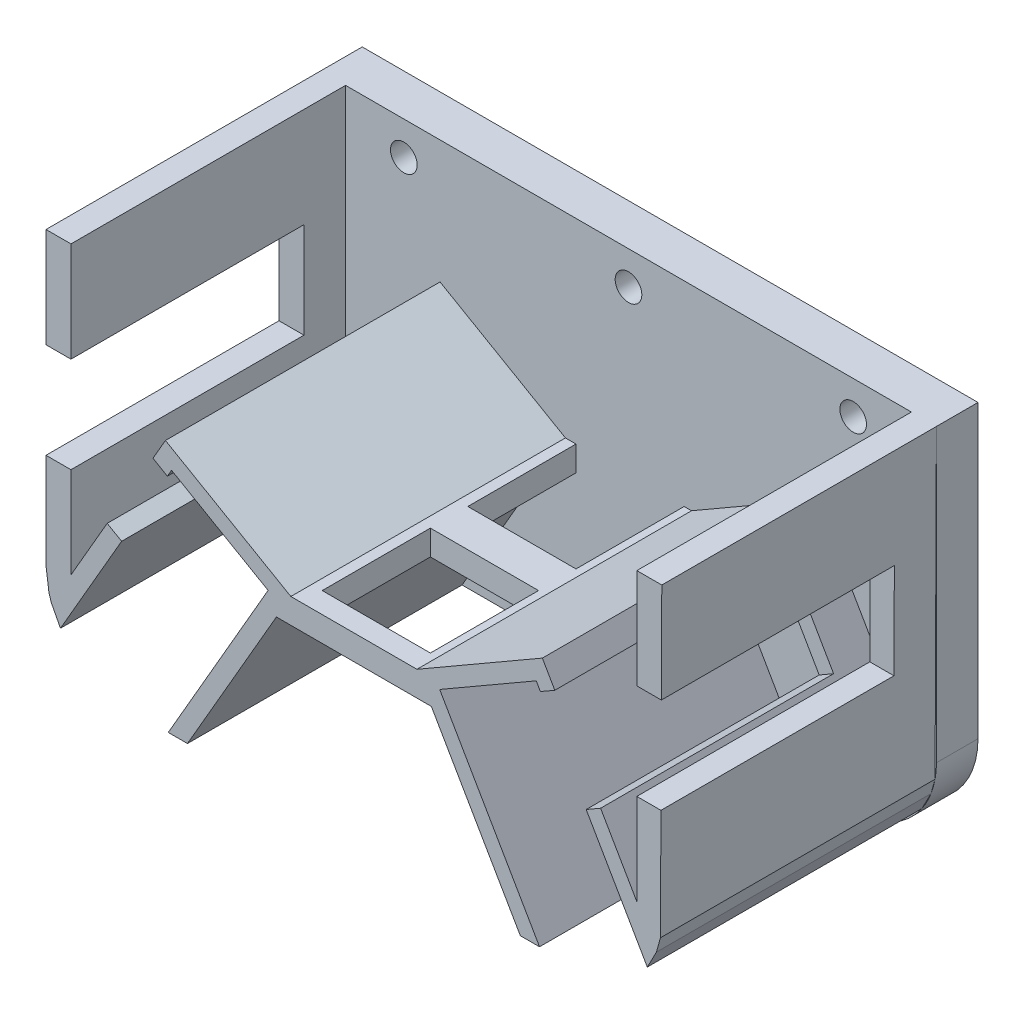
SolidWorks part; units mm, degrees
ref_plane "前视基准面" through (0, 0, 0) normal (0, 0, 1) x (1, 0, 0)
ref_plane "上视基准面" through (0, 0, 0) normal (0, 1, 0) x (1, 0, 0)
ref_plane "右视基准面" through (0, 0, 0) normal (1, 0, 0) x (0, 0, -1)
other "Configuration Table"
sketch "草图1" plane through (0, 0, 0) normal (0, 0, 1) x (1, 0, 0)
  line L0 (-37, -22.5) -> (37, -22.5)
  line L1 (-37, 22.5) -> (37, 22.5)
  line L2 (-37, 22.5) -> (-37, -22.5)
  line L4 (37, 22.5) -> (37, -22.5)
  line L5 (0, -22.5) -> (0, 22.5) construction
  line L6 (-37, 0) -> (37, 0) construction
  point P0 (0, 0)
  point P8 (37, -22.5)
  dimension "D1" = 74
  dimension "D2" = 45
extrude "凸台-拉伸1" add sketch "草图1" along normal blind 5
fillet "圆角1" radius 10 1 edges at (-37, -22.5, 2.5)
fillet "圆角2" radius 10 1 edges at (37, -22.5, 2.5)
sketch "草图4" plane through (0, 0, 5) normal (0, 0, 1) x (1, 0, 0)
  line L0 (-35.2618, -18.1341) -> (-21.9141, 4.9846)
  line L1 (-21.9141, 4.9846) -> (-10.3094, -1.7154)
  line L2 (-10.3094, -1.7154) -> (-22.3094, -22.5)
  line L4 (0, 0) -> (0, 22.5) construction
  line L6 (-20, -22.5) -> (-7.5774, -0.9833)
  line L7 (-27, -22.5) -> (27, -22.5) construction
  line L8 (-7.5774, -0.9833) -> (-22.6462, 7.7167)
  line L9 (-22.6462, 7.7167) -> (-36.3563, -16.0299)
  line L11 (-22.3094, -22.5) -> (-20, -22.5)
  line L20 (-36.3563, -16.0299) -> (-35.2618, -18.1341)
  line L21 (36.3563, -16.0299) -> (35.2618, -18.1341)
  line L22 (22.3094, -22.5) -> (20, -22.5)
  line L23 (22.6462, 7.7167) -> (36.3563, -16.0299)
  line L24 (7.5774, -0.9833) -> (22.6462, 7.7167)
  line L25 (20, -22.5) -> (7.5774, -0.9833)
  line L26 (10.3094, -1.7154) -> (22.3094, -22.5)
  line L27 (21.9141, 4.9846) -> (10.3094, -1.7154)
  line L28 (35.2618, -18.1341) -> (21.9141, 4.9846)
  arc A1 (-37, -12.5) -> (-27, -22.5) centre (-27, -12.5) ccw construction
  point P2 (-36.3563, -16.0299)
  point P23 (36.3563, -16.0299)
  dimension "D1" = 13.4
  dimension "D2" = 24
  dimension "D3" = 2
  dimension "D4" = 2
  dimension "D5" = 2
  dimension "D6" = 60
  dimension "D7" = 20
extrude "凸台-拉伸3" add sketch "草图4" along normal blind 33
sketch "草图5" plane through (0, 0, 5) normal (0, 0, 1) x (1, 0, 0)
  line L0 (-7.5774, -0.9833) -> (7.5774, -0.9833)
  line L1 (7.5774, -0.9833) -> (9.3094, -3.9833)
  line L2 (7.5774, -0.9833) -> (20, -22.5) construction
  line L3 (9.3094, -3.9833) -> (-9.3094, -3.9833)
  line L4 (-20, -22.5) -> (-7.5774, -0.9833) construction
  line L5 (-9.3094, -3.9833) -> (-7.5774, -0.9833)
  dimension "D1" = 3
extrude "凸台-拉伸4" add sketch "草图5" along normal blind 33
sketch "草图6" plane through (0, -3.9833, 0) normal (0, -1, 0) x (1, 0, 0)
  line L0 (-20, 5) -> (20, 5) construction
  line L1 (-6.3094, 35.5) -> (6.6906, 35.5)
  line L2 (-6.3094, 35.5) -> (-6.3094, 22.5)
  line L3 (-6.3094, 22.5) -> (6.6906, 22.5)
  line L4 (6.6906, 35.5) -> (6.6906, 22.5)
  line L5 (-6.3094, 18) -> (6.6906, 18)
  line L6 (-6.3094, 18) -> (-6.3094, 5)
  line L7 (-6.3094, 5) -> (6.6906, 5)
  line L8 (6.6906, 18) -> (6.6906, 5)
  line L9 (-9.3094, 38) -> (-9.3094, 5) construction
  line L10 (-9.3094, 38) -> (9.3094, 38) construction
  dimension "D1" = 13
  dimension "D2" = 3
  dimension "D3" = 13
  dimension "D4" = 13
  dimension "D5" = 2.5
  dimension "D6" = 13
extrude "切除-拉伸1" cut sketch "草图6" against normal through all
sketch "草图8" plane through (0, 0, 38) normal (0, 0, 1) x (1, 0, 0)
  line L0 (-29.6462, -4.4077) -> (-24.1462, 5.1186)
  line L1 (-22.6462, 7.7167) -> (-36.3563, -16.0299) construction
  line L2 (-24.1462, 5.1186) -> (-22.4141, 4.1186)
  line L3 (-35.2618, -18.1341) -> (-21.9141, 4.9846) construction
  line L4 (-22.4141, 4.1186) -> (-27.9141, -5.4077)
  line L5 (-27.9141, -5.4077) -> (-29.6462, -4.4077)
  line L6 (0, 0) -> (0, 25.4331) construction
  line L7 (-7.5774, -0.9833) -> (-22.6462, 7.7167) construction
  line L8 (27.9141, -5.4077) -> (29.6462, -4.4077)
  line L9 (22.4141, 4.1186) -> (27.9141, -5.4077)
  line L10 (24.1462, 5.1186) -> (22.4141, 4.1186)
  line L11 (29.6462, -4.4077) -> (24.1462, 5.1186)
  dimension "D1" = 3
  dimension "D2" = 11
extrude "切除-拉伸3" cut sketch "草图8" against normal blind 28
sketch "草图9" plane through (0, 0, 5) normal (0, 0, 1) x (1, 0, 0)
  line L2 (37, 22.5) -> (-37, 22.5) construction
  line L3 (-34, 22.5) -> (-37, 22.5)
  line L7 (0, 0) -> (0, 41.014) construction
  line L8 (36.3563, -16.0299) -> (34, -11.9487)
  line L9 (36.8378, -14.2941) -> (36.3563, -16.0299)
  line L10 (37, 22.5) -> (36.8378, -14.2941)
  line L11 (34, 22.5) -> (37, 22.5)
  line L12 (34, -11.9487) -> (34, 22.5)
  line L13 (-37, 22.5) -> (-37, -12.5)
  line L14 (-37, -12.5) -> (-36.6387, -15.1638)
  line L15 (-36.6387, -15.1638) -> (-36.3563, -16.0299)
  line L16 (-34, 22.5) -> (-34, -11.9487)
  line L17 (-22.6462, 7.7167) -> (-36.3563, -16.0299) construction
  line L18 (-34, -11.9487) -> (-36.3563, -16.0299)
  arc A1 (-37, -12.5) -> (-36.3563, -16.0299) centre (-27, -12.5) ccw construction
  dimension "D1" = 3
extrude "凸台-拉伸5" add sketch "草图9" along normal blind 33
sketch "草图10" plane through (0, 0, 38) normal (0, 0, 1) x (1, 0, 0)
  line L0 (-37, 22.5) -> (-37, -12.5) construction
  line L1 (-37, 10.5) -> (-34, 10.5)
  line L2 (-37, 10.5) -> (-37, -1)
  line L3 (-37, -1) -> (-34, -1)
  line L4 (-34, 10.5) -> (-34, -1)
  line L5 (-34, -11.9487) -> (-34, 22.5) construction
  line L6 (-34, 22.5) -> (-37, 22.5) construction
  line L7 (0, 0) -> (0, 29.9906) construction
  line L8 (34, 10.5) -> (34, -1)
  line L9 (37, -1) -> (34, -1)
  line L10 (37, 10.5) -> (37, -1)
  line L11 (37, 10.5) -> (34, 10.5)
  dimension "D1" = 12
  dimension "D2" = 11.5
extrude "切除-拉伸4" cut sketch "草图10" against normal blind 28
sketch "草图11" plane through (0, 0, 5) normal (0, 0, 1) x (1, 0, 0)
  line L0 (34, 22.5) -> (-34, 22.5) construction
  line L1 (-37, 22.5) -> (-37, 10.5) construction
  circle A0 centre (-27, 18.5) radius 1.6
  circle A1 centre (0, 18.5) radius 1.6
  circle A2 centre (27, 18.5) radius 1.6
  dimension "D2" = 3.2
  dimension "D3" = 10
  dimension "D4" = 3.2
  dimension "D5" = 3.2
  dimension "D9" = 4
  dimension "D1" = 4
  dimension "D6" = 27
  dimension "D7" = 4
  dimension "D8" = 27
extrude "切除-拉伸5" cut sketch "草图11" against normal blind 10
